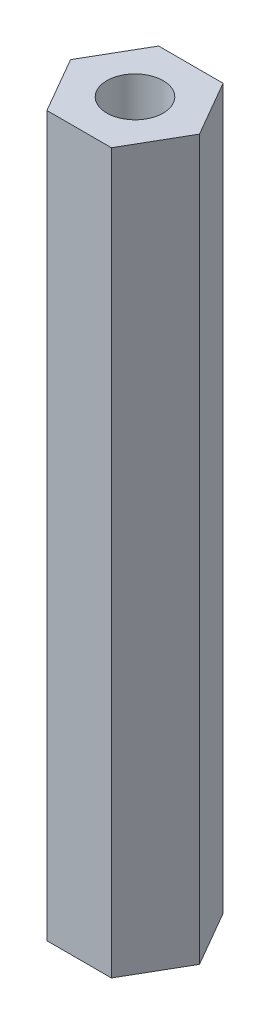
SolidWorks part; units mm, degrees
ref_plane "Front Plane" through (0, 0, 0) normal (0, 0, 1) x (1, 0, 0)
ref_plane "Top Plane" through (0, 0, 0) normal (0, 1, 0) x (1, 0, 0)
ref_plane "Right Plane" through (0, 0, 0) normal (1, 0, 0) x (0, 0, -1)
sketch "Sketch1" plane through (0, 0, 0) normal (0, 1, 0) x (1, 0, 0)
  line L1 (2.6905, 0) -> (1.3452, 2.33)
  line L2 (1.3452, 2.33) -> (-1.3452, 2.33)
  line L3 (-1.3452, 2.33) -> (-2.6905, 0)
  line L4 (-2.6905, 0) -> (-1.3452, -2.33)
  line L5 (-1.3452, -2.33) -> (1.3452, -2.33)
  line L6 (1.3452, -2.33) -> (2.6905, 0)
  circle A0 centre (0, 0) radius 2.33 construction
  circle A1 centre (0, 0) radius 1.175
  point P1 (2.0178, -1.165)
  dimension "D2" = 2.35
  dimension "D1" = 4.66
extrude "Boss-Extrude1" add sketch "Sketch1" along normal blind 30
